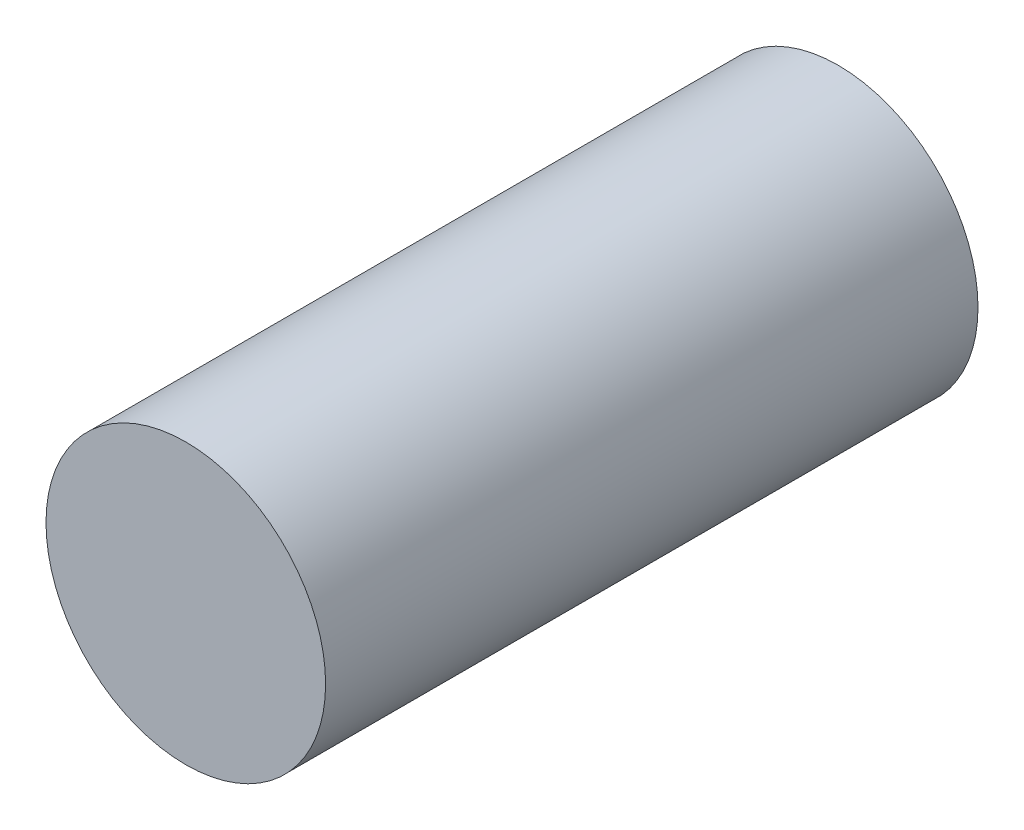
SolidWorks part; units mm, degrees
ref_plane "Front Plane" through (0, 0, 0) normal (0, 0, 1) x (1, 0, 0)
ref_plane "Top Plane" through (0, 0, 0) normal (0, 1, 0) x (1, 0, 0)
ref_plane "Right Plane" through (0, 0, 0) normal (1, 0, 0) x (0, 0, -1)
sketch "Sketch1" plane through (0, 0, 0) normal (0, 0, 1) x (1, 0, 0)
  circle A0 centre (0, 0) radius 1.5
  dimension "D1" = 3
extrude "Boss-Extrude1" add sketch "Sketch1" along normal blind 7
